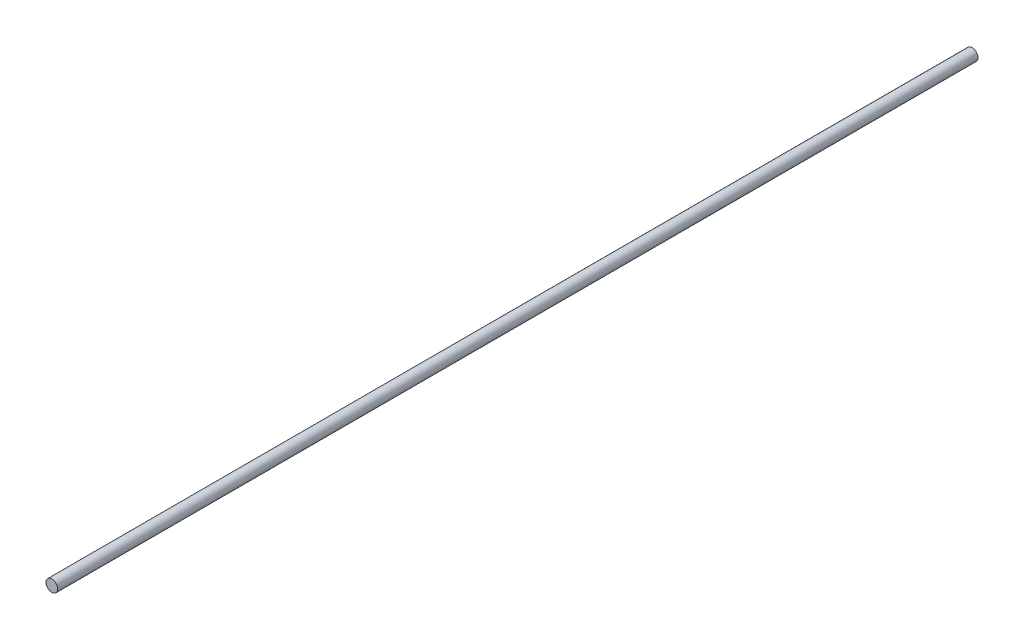
SolidWorks part; units mm, degrees
material "Hexcel AS4C (3000 filamentos)"
ref_plane "Alzado" through (0, 0, 0) normal (0, 0, 1) x (1, 0, 0)
ref_plane "Planta" through (0, 0, 0) normal (0, 1, 0) x (1, 0, 0)
ref_plane "Vista lateral" through (0, 0, 0) normal (1, 0, 0) x (0, 0, -1)
sketch "Croquis1" plane through (0, 0, 0) normal (0, 0, 1) x (1, 0, 0)
  circle A0 centre (0, 0) radius 3.175
  dimension "D1" = 6.35
extrude "Saliente-Extruir1" add sketch "Croquis1" along normal blind 500
